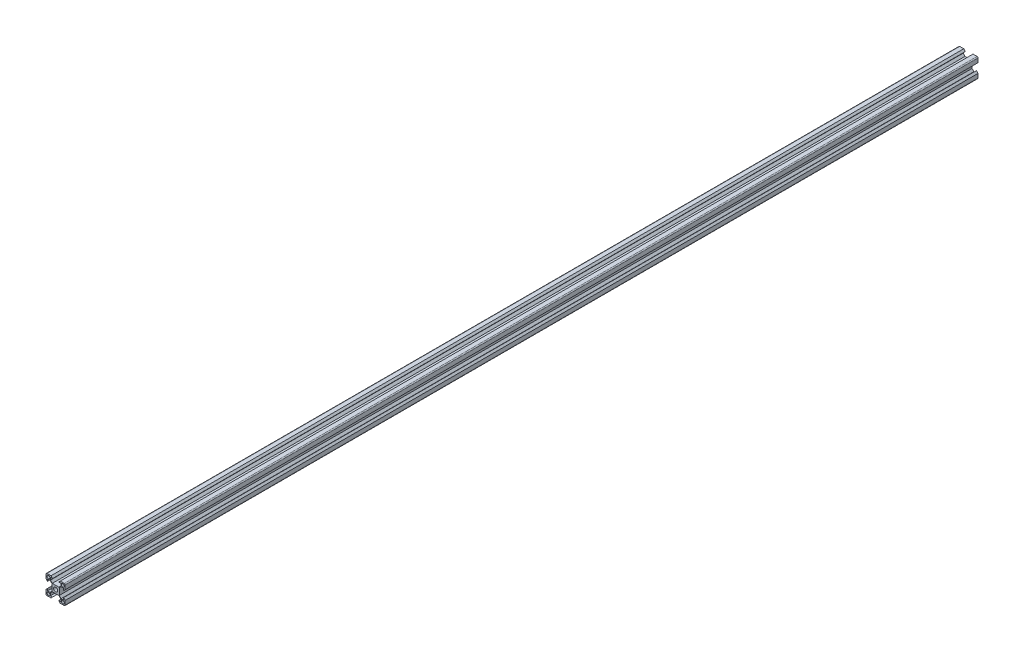
SolidWorks part; units mm, degrees
material "铝管"
ref_plane "前视基准面" through (0, 0, 0) normal (0, 0, 1) x (1, 0, 0)
ref_plane "上视基准面" through (0, 0, 0) normal (0, 1, 0) x (1, 0, 0)
ref_plane "右视基准面" through (0, 0, 0) normal (1, 0, 0) x (0, 0, -1)
sketch "草图1" plane through (0, 0, 0) normal (0, 0, 1) x (1, 0, 0)
  line L0 (0, 0) -> (-40.5659, 40.5659) construction
  line L1 (0, 0) -> (0, 75.5033) construction
  line L2 (-10, 10) -> (-10, 4.8)
  line L3 (-10, 4.8) -> (-8.34, 3.14)
  line L4 (-8.34, 3.14) -> (-8.34, 5.4)
  line L5 (-5.7536, 5.4) -> (-3.8, 3.4464)
  line L6 (-3.8, 3.4464) -> (-3.8, -3.4464)
  line L7 (-3.8, 0) -> (15.6715, 0) construction
  line L8 (-5.4, 8.34) -> (-5.4, 5.7536)
  line L9 (-3.4464, 3.8) -> (3.4464, 3.8)
  line L10 (-5.4, 5.7536) -> (-3.4464, 3.8)
  line L11 (-3.14, 8.34) -> (-5.4, 8.34)
  line L12 (-8.34, 5.4) -> (-5.7536, 5.4)
  line L13 (-4.8, 10) -> (-3.14, 8.34)
  line L14 (-10, 10) -> (-4.8, 10)
  line L15 (-10, -10) -> (-4.8, -10)
  line L16 (-4.8, -10) -> (-3.14, -8.34)
  line L17 (-8.34, -5.4) -> (-5.7536, -5.4)
  line L18 (-3.14, -8.34) -> (-5.4, -8.34)
  line L19 (-5.4, -5.7536) -> (-3.4464, -3.8)
  line L20 (-3.4464, -3.8) -> (3.4464, -3.8)
  line L21 (-5.4, -8.34) -> (-5.4, -5.7536)
  line L22 (-5.7536, -5.4) -> (-3.8, -3.4464)
  line L23 (-8.34, -3.14) -> (-8.34, -5.4)
  line L24 (-10, -4.8) -> (-8.34, -3.14)
  line L25 (-10, -10) -> (-10, -4.8)
  line L26 (10, -10) -> (10, -4.8)
  line L27 (10, -4.8) -> (8.34, -3.14)
  line L28 (8.34, -3.14) -> (8.34, -5.4)
  line L29 (5.7536, -5.4) -> (3.8, -3.4464)
  line L30 (5.4, -8.34) -> (5.4, -5.7536)
  line L31 (5.4, -5.7536) -> (3.4464, -3.8)
  line L32 (3.14, -8.34) -> (5.4, -8.34)
  line L33 (8.34, -5.4) -> (5.7536, -5.4)
  line L34 (4.8, -10) -> (3.14, -8.34)
  line L35 (10, -10) -> (4.8, -10)
  line L36 (10, 10) -> (4.8, 10)
  line L37 (4.8, 10) -> (3.14, 8.34)
  line L38 (8.34, 5.4) -> (5.7536, 5.4)
  line L39 (3.14, 8.34) -> (5.4, 8.34)
  line L40 (5.4, 5.7536) -> (3.4464, 3.8)
  line L41 (5.4, 8.34) -> (5.4, 5.7536)
  line L42 (3.8, 3.4464) -> (3.8, -3.4464)
  line L43 (5.7536, 5.4) -> (3.8, 3.4464)
  line L44 (8.34, 3.14) -> (8.34, 5.4)
  line L45 (10, 4.8) -> (8.34, 3.14)
  line L46 (10, 10) -> (10, 4.8)
  circle A0 centre (-7.5, 7.5) radius 1.5
  circle A1 centre (0, 0) radius 2.1
  circle A2 centre (-7.5, -7.5) radius 1.5
  circle A3 centre (7.5, -7.5) radius 1.5
  circle A4 centre (7.5, 7.5) radius 1.5
  point P54 (0, -3.8)
  point P64 (0, 3.8)
  dimension "D6" = 3
  dimension "D7" = 7.5
  dimension "D9" = 4.2
  dimension "D1" = 45
  dimension "D2" = 4.8
  dimension "D3" = 3.8
  dimension "D4" = 10
  dimension "D5" = 5.4
  dimension "D8" = 3.14
  dimension "D10" = 10
  dimension "D11" = 0.5
extrude "凸台-拉伸1" add sketch "草图1" along normal blind 950
fillet "圆角1" radius 1 4 edges at (-10, -10, 475) (10, -10, 475) (-10, 10, 475) (10, 10, 475)
